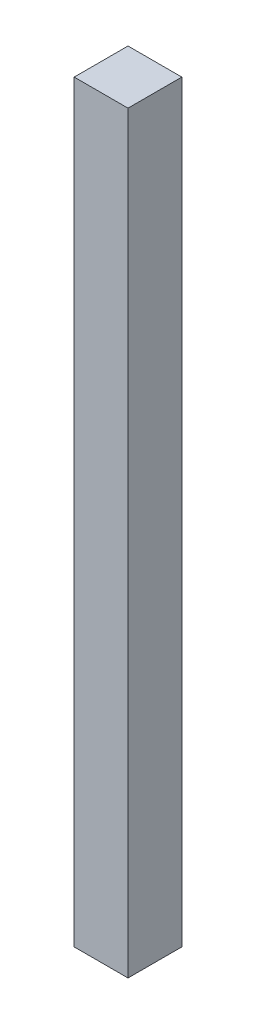
SolidWorks part; units mm, degrees
ref_plane "Front Plane" through (0, 0, 0) normal (0, 0, 1) x (1, 0, 0)
ref_plane "Top Plane" through (0, 0, 0) normal (0, 1, 0) x (1, 0, 0)
ref_plane "Right Plane" through (0, 0, 0) normal (1, 0, 0) x (0, 0, -1)
sketch "Sketch1" plane through (0, 0, 0) normal (0, 1, 0) x (1, 0, 0)
  line L1 (-12.7, -12.7) -> (12.7, -12.7)
  line L2 (-12.7, -12.7) -> (-12.7, 12.7)
  line L3 (-12.7, 12.7) -> (12.7, 12.7)
  line L4 (12.7, -12.7) -> (12.7, 12.7)
  line L5 (-12.7, -12.7) -> (12.7, 12.7) construction
  line L6 (-12.7, 12.7) -> (12.7, -12.7) construction
  point P0 (0, 0)
  dimension "D1" = 25.4
extrude "Boss-Extrude1" add sketch "Sketch1" along normal mid plane 355.6
